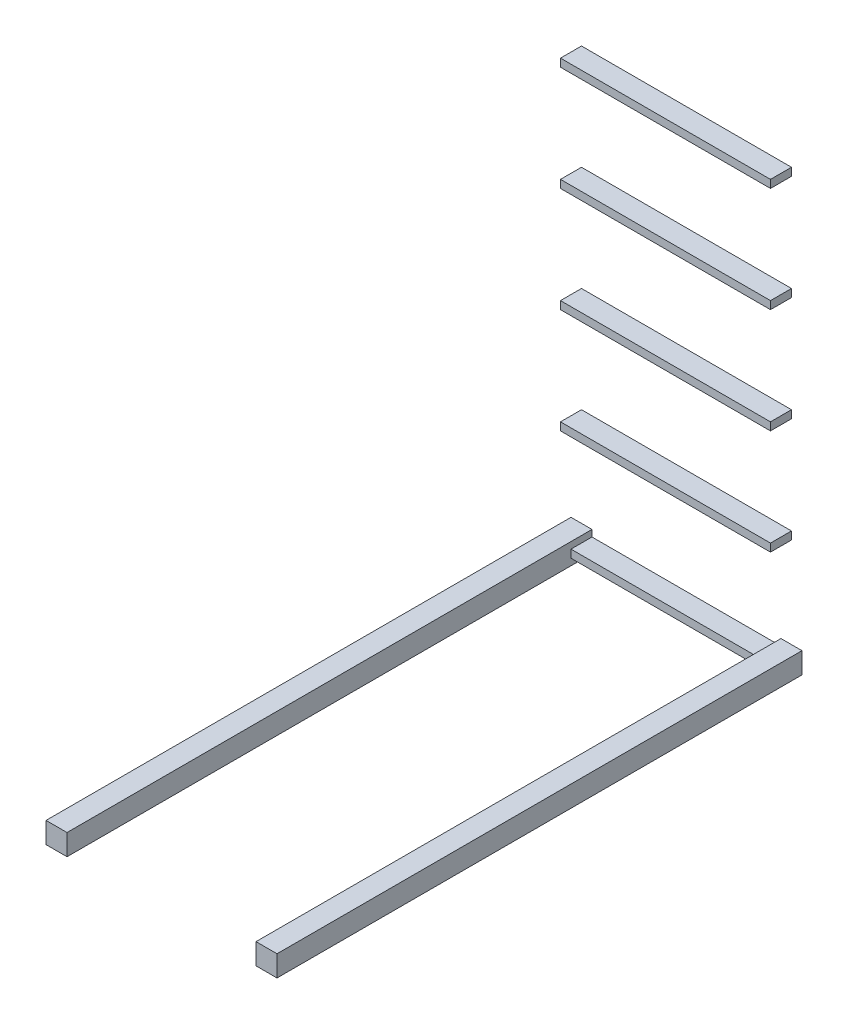
SolidWorks part; units mm, degrees
ref_plane "前视基准面" through (0, 0, 0) normal (0, 0, 1) x (1, 0, 0)
ref_plane "上视基准面" through (0, 0, 0) normal (0, 1, 0) x (1, 0, 0)
ref_plane "右视基准面" through (0, 0, 0) normal (1, 0, 0) x (0, 0, -1)
other "Configuration Table"
sketch "草图1" plane through (0, 0, 0) normal (0, 0, 1) x (1, 0, 0)
  line L1 (-440, -40) -> (-360, -40)
  line L2 (-440, -40) -> (-440, 40)
  line L3 (-440, 40) -> (-360, 40)
  line L4 (-360, -40) -> (-360, 40)
  line L5 (-440, -40) -> (-360, 40) construction
  line L6 (-440, 40) -> (-360, -40) construction
  point P0 (-400, 0)
extrude "凸台-拉伸1" add sketch "草图1" along normal blind 2000
sketch "草图2" plane through (0, 0, 0) normal (0, 0, 1) x (1, 0, 0)
  line L1 (360, -40) -> (440, -40)
  line L2 (360, -40) -> (360, 40)
  line L3 (360, 40) -> (440, 40)
  line L4 (440, -40) -> (440, 40)
  line L5 (360, -40) -> (440, 40) construction
  line L6 (360, 40) -> (440, -40) construction
  point P0 (400, 0)
extrude "凸台-拉伸2" add sketch "草图2" along normal blind 2000
sketch "草图3" plane through (0, 0, 0) normal (0, 0, 1) x (1, 0, 0)
  line L1 (-400, -15) -> (400, -15)
  line L2 (-400, -15) -> (-400, 15)
  line L3 (-400, 15) -> (400, 15)
  line L4 (400, -15) -> (400, 15)
  line L5 (-400, -15) -> (400, 15) construction
  line L6 (-400, 15) -> (400, -15) construction
  point P0 (0, 0)
extrude "凸台-拉伸3" add sketch "草图3" along normal blind 80
sketch "草图4" plane through (0, 0, 0) normal (0, 0, 1) x (1, 0, 0)
  line L1 (-400, 385) -> (400, 385)
  line L2 (-400, 385) -> (-400, 415)
  line L3 (-400, 415) -> (400, 415)
  line L4 (400, 385) -> (400, 415)
  line L5 (-400, 385) -> (400, 415) construction
  line L6 (-400, 415) -> (400, 385) construction
  point P0 (0, 400)
extrude "凸台-拉伸4" add sketch "草图4" along normal blind 80
sketch "草图5" plane through (0, 0, 0) normal (0, 0, 1) x (1, 0, 0)
  line L1 (-400, 785) -> (400, 785)
  line L2 (-400, 785) -> (-400, 815)
  line L3 (-400, 815) -> (400, 815)
  line L4 (400, 785) -> (400, 815)
  line L5 (-400, 785) -> (400, 815) construction
  line L6 (-400, 815) -> (400, 785) construction
  point P0 (0, 800)
extrude "凸台-拉伸5" add sketch "草图5" along normal blind 80
sketch "草图6" plane through (0, 0, 0) normal (0, 0, 1) x (1, 0, 0)
  line L1 (-400, 1185) -> (400, 1185)
  line L2 (-400, 1185) -> (-400, 1215)
  line L3 (-400, 1215) -> (400, 1215)
  line L4 (400, 1185) -> (400, 1215)
  line L5 (-400, 1185) -> (400, 1215) construction
  line L6 (-400, 1215) -> (400, 1185) construction
  point P0 (0, 1200)
extrude "凸台-拉伸6" add sketch "草图6" along normal blind 80
sketch "草图7" plane through (0, 0, 0) normal (0, 0, 1) x (1, 0, 0)
  line L1 (-400, 1585) -> (400, 1585)
  line L2 (-400, 1585) -> (-400, 1615)
  line L3 (-400, 1615) -> (400, 1615)
  line L4 (400, 1585) -> (400, 1615)
  line L5 (-400, 1585) -> (400, 1615) construction
  line L6 (-400, 1615) -> (400, 1585) construction
  point P0 (0, 1600)
extrude "凸台-拉伸7" add sketch "草图7" along normal blind 80
